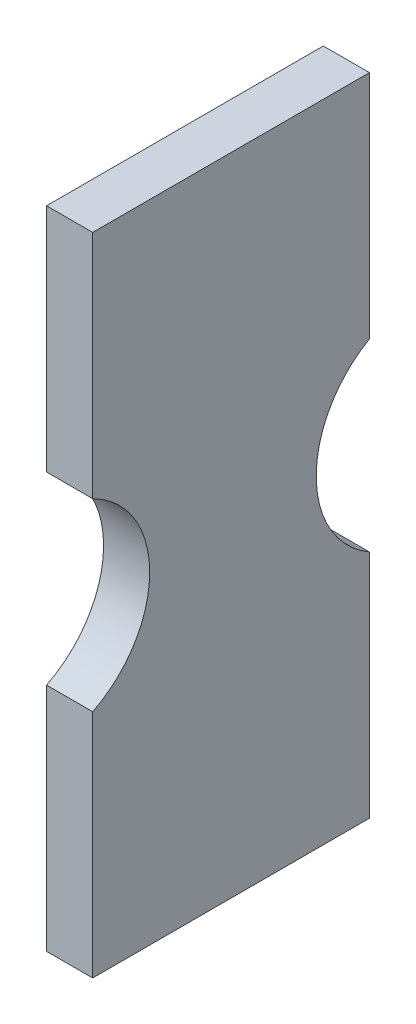
SolidWorks part; units mm, degrees
ref_plane "Front Plane" through (0, 0, 0) normal (1, 0, 0) x (0, 1, 0)
ref_plane "Top Plane" through (0, 0, 0) normal (0, 0, 1) x (0, 1, 0)
ref_plane "Right Plane" through (0, 0, 0) normal (0, 1, 0) x (-1, 0, 0)
sketch "Sketch1" plane through (0, 0, 0) normal (1, 0, 0) x (0, 1, 0)
  line L1 (0, 0) -> (88.9, 0)
  line L2 (0, 0) -> (0, 38.1)
  line L3 (0, 38.1) -> (88.9, 38.1)
  line L4 (88.9, 0) -> (88.9, 38.1)
  dimension "D1" = 38.1
  dimension "D2" = 88.9
extrude "Boss-Extrude1" add sketch "Sketch1" along normal blind 6.35
sketch "Sketch2" plane through (6.35, 0, 0) normal (1, 0, 0) x (0, 1, 0)
  line L0 (31.75, 38.1) -> (57.15, 38.1)
  line L1 (31.75, 0) -> (57.15, 0)
  line L3 (88.9, 38.1) -> (0, 38.1) construction
  line L4 (0, 0) -> (88.9, 0) construction
  arc A2 (31.75, 38.1) -> (57.15, 38.1) centre (44.45, 44.45) ccw
  arc A3 (31.75, 0) -> (57.15, 0) centre (44.45, -7.3441) cw
  dimension "D3" = 14.199
extrude "Cut-Extrude2" cut sketch "Sketch2" against normal blind 6.35
